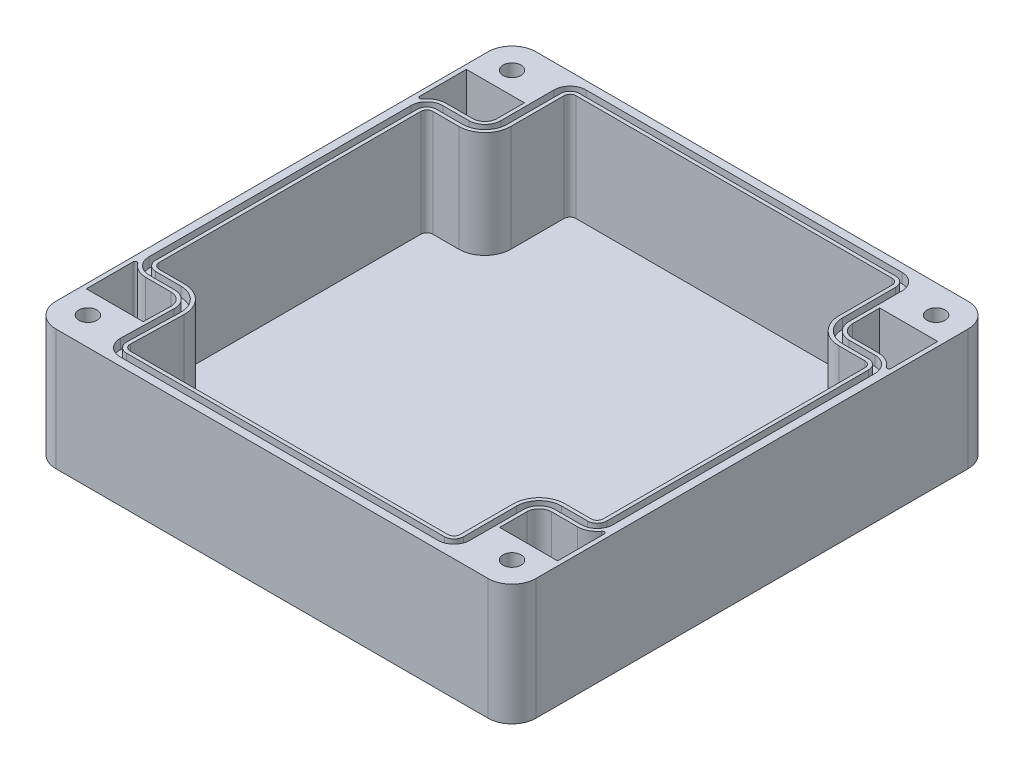
SolidWorks part; units mm, degrees
other "陽光" [suppressed]
material "ABS"
ref_plane "前基準面" through (0, 0, 0) normal (0, 0, 1) x (1, 0, 0)
ref_plane "上基準面" through (0, 0, 0) normal (0, 1, 0) x (1, 0, 0)
ref_plane "右基準面" through (0, 0, 0) normal (1, 0, 0) x (0, 0, -1)
other "ABS"
sketch "草圖1" plane through (0, 0, 0) normal (0, 1, 0) x (1, 0, 0)
  line L1 (6.3409, 120.3409) -> (114.3409, 120.3409)
  line L2 (0.3409, 114.3409) -> (0.3409, 6.3409)
  line L3 (6.3409, 0.3409) -> (114.3409, 0.3409)
  line L4 (120.3409, 114.3409) -> (120.3409, 6.3409)
  circle A0 centre (7.3409, 113.3409) radius 2.25
  circle A2 centre (113.3409, 113.3409) radius 2.25
  circle A5 centre (7.3409, 7.3409) radius 2.25
  circle A7 centre (113.3409, 7.3409) radius 2.25
  arc A8 (114.3409, 120.3409) -> (120.3409, 114.3409) centre (114.3409, 114.3409) cw
  arc A9 (120.3409, 6.3409) -> (114.3409, 0.3409) centre (114.3409, 6.3409) cw
  arc A10 (6.3409, 0.3409) -> (0.3409, 6.3409) centre (6.3409, 6.3409) cw
  arc A11 (0.3409, 114.3409) -> (6.3409, 120.3409) centre (6.3409, 114.3409) cw
  point P37 (120.3409, 120.3409)
  point P42 (0.3409, 0.3409)
  point P45 (0.3409, 120.3409)
  dimension "D3" = 106
  dimension "D4" = 7
  dimension "D7" = 7
  dimension "D13" = 6
  dimension "D6" = 106
  dimension "D2" = 120
  dimension "D8" = 7
  dimension "D10" = 120
  dimension "D12" = 7
extrude "填料-伸長1" add sketch "草圖1" along normal blind 30.25
sketch "草圖2" plane through (0, 30.25, 0) normal (0, 1, 0) x (1, 0, 0)
  line L1 (15.9409, 101.0538) -> (15.9409, 107.8409)
  line L21 (6.3409, 97.9538) -> (12.8409, 97.9538)
  line L23 (6.3281, 22.7581) -> (12.7279, 22.7414)
  line L25 (15.8189, 19.567) -> (15.6575, 12.8409)
  line L29 (0.3409, 114.3409) -> (0.3409, 6.3409) construction
  line L34 (114.3409, 120.3409) -> (6.3409, 120.3409) construction
  line L35 (99.8409, 115.8409) -> (20.8409, 115.8409)
  line L36 (19.3409, 101.0538) -> (19.3409, 114.3409)
  line L37 (6.3409, 94.5538) -> (12.8409, 94.5538)
  line L42 (4.8409, 93.0538) -> (4.8409, 27.6581)
  line L47 (0.3409, 60.3409) -> (120.3409, 60.3409) construction
  line L48 (104.7409, 19.628) -> (104.7409, 12.8409)
  line L49 (120.3409, 6.3409) -> (120.3409, 114.3409) construction
  line L50 (60.3409, 120.3409) -> (60.3409, 0.3409) construction
  line L51 (114.3409, 22.728) -> (107.8409, 22.728)
  line L52 (6.3409, 0.3409) -> (114.3409, 0.3409) construction
  line L60 (114.3409, 97.9538) -> (107.8409, 97.9538)
  line L61 (104.7409, 101.0538) -> (104.7409, 107.8409)
  line L62 (1.4409, 96.1843) -> (1.4409, 107.8409)
  line L63 (1.4409, 107.8409) -> (15.9409, 107.8409)
  line L64 (6.337, 26.1581) -> (12.7368, 26.1414)
  line L65 (1.4409, 24.5276) -> (1.4409, 12.8409)
  line L66 (1.4409, 12.8409) -> (15.6575, 12.8409)
  line L67 (119.2409, 96.1843) -> (119.2409, 107.8409)
  line L68 (119.2409, 107.8409) -> (104.7409, 107.8409)
  line L69 (119.2409, 24.4975) -> (119.2409, 12.8409)
  line L70 (119.2409, 12.8409) -> (104.7409, 12.8409)
  line L71 (19.2179, 19.4855) -> (18.9034, 6.3769)
  line L72 (20.403, 4.8409) -> (99.8409, 4.8409)
  line L73 (101.3409, 19.628) -> (101.3409, 6.3409)
  line L74 (114.3409, 26.128) -> (107.8409, 26.128)
  line L75 (115.8409, 27.628) -> (115.8409, 93.0538)
  line L76 (114.3409, 94.5538) -> (107.8409, 94.5538)
  line L77 (101.3409, 101.0538) -> (101.3409, 114.3409)
  arc A42 (19.3409, 114.3409) -> (20.8409, 115.8409) centre (20.8409, 114.3409) cw
  arc A43 (1.4409, 24.5276) -> (2.3483, 24.8175) centre (1.9409, 24.5276) cw
  arc A44 (12.8409, 94.5538) -> (19.3409, 101.0538) centre (12.8409, 101.0538) ccw
  arc A45 (2.3483, 95.8944) -> (1.4409, 96.1843) centre (1.9409, 96.1843) cw
  arc A51 (12.8409, 97.9538) -> (15.9409, 101.0538) centre (12.8409, 101.0538) ccw
  arc A52 (6.3409, 97.9538) -> (2.3483, 95.8944) centre (6.3409, 93.0538) ccw
  arc A53 (6.3281, 22.7581) -> (2.3483, 24.8175) centre (6.3409, 27.6581) cw
  arc A54 (15.8189, 19.567) -> (12.7279, 22.7414) centre (12.7198, 19.6414) ccw
  arc A57 (104.7409, 19.628) -> (107.8409, 22.728) centre (107.8409, 19.628) cw
  arc A58 (114.3409, 22.728) -> (118.3335, 24.7874) centre (114.3409, 27.628) ccw
  arc A59 (114.3409, 97.9538) -> (118.3335, 95.8944) centre (114.3409, 93.0538) cw
  arc A60 (107.8409, 97.9538) -> (104.7409, 101.0538) centre (107.8409, 101.0538) cw
  arc A62 (6.3409, 94.5538) -> (4.8409, 93.0538) centre (6.3409, 93.0538) ccw
  arc A63 (6.337, 26.1581) -> (4.8409, 27.6581) centre (6.3409, 27.6581) cw
  arc A64 (19.2179, 19.4855) -> (12.7368, 26.1414) centre (12.7198, 19.6414) ccw
  arc A65 (18.9034, 6.3769) -> (20.403, 4.8409) centre (20.403, 6.3409) ccw
  arc A66 (101.3409, 6.3409) -> (99.8409, 4.8409) centre (99.8409, 6.3409) cw
  arc A67 (119.2409, 96.1843) -> (118.3335, 95.8944) centre (118.7409, 96.1843) cw
  arc A68 (101.3409, 19.628) -> (107.8409, 26.128) centre (107.8409, 19.628) cw
  arc A69 (118.3335, 24.7874) -> (119.2409, 24.4975) centre (118.7409, 24.4975) cw
  arc A70 (114.3409, 26.128) -> (115.8409, 27.628) centre (114.3409, 27.628) ccw
  arc A71 (114.3409, 94.5538) -> (115.8409, 93.0538) centre (114.3409, 93.0538) cw
  arc A72 (107.8409, 94.5538) -> (101.3409, 101.0538) centre (107.8409, 101.0538) cw
  arc A73 (101.3409, 114.3409) -> (99.8409, 115.8409) centre (99.8409, 114.3409) ccw
  point P41 (102.8409, 96.0538)
  point P44 (17.8409, 96.0538)
  point P47 (102.8409, 24.628)
  point P50 (17.8409, 24.628)
  point P52 (99.8409, 3.3409)
  point P54 (117.3409, 27.628)
  point P56 (117.3409, 93.0538)
  point P57 (104.8409, 17.8409)
  point P59 (110.2409, 20.8409)
  point P60 (110.2409, 24.0409)
  point P61 (113.4409, 24.0409)
  point P62 (113.4409, 65.9246)
  point P63 (110.2409, 65.9246)
  point P64 (110.2409, 69.1246)
  point P67 (104.8409, 72.1246)
  point P68 (104.8409, 85.2409)
  point P69 (101.6409, 85.2409)
  point P70 (101.6409, 88.4409)
  point P73 (10.8409, 85.2409)
  point P74 (10.8409, 72.8409)
  point P75 (3.3409, 93.0538)
  point P77 (5.4409, 69.8409)
  point P78 (5.4409, 66.6409)
  point P79 (2.2409, 66.6409)
  point P80 (2.2409, 24.0409)
  point P81 (5.4409, 24.0409)
  point P82 (5.4409, 20.8409)
  point P83 (3.3409, 27.6581)
  point P85 (10.5331, 17.8409)
  point P86 (10.5331, 5.4409)
  point P87 (20.403, 3.3409)
  point P88 (99.8409, 119.2409)
  point P89 (20.8409, 119.2409)
  point P91 (104.8409, 5.4409)
  point P92 (15.9409, 114.3409)
  point P98 (1.4409, 93.0538)
  point P105 (15.5044, 6.4585)
  point P107 (20.403, 1.4409)
  point P108 (99.8409, 1.4409)
  point P110 (104.7409, 6.3409)
  point P116 (119.2409, 27.628)
  point P117 (119.2409, 93.0538)
  point P123 (104.7409, 114.3409)
extrude "除料-伸長1" cut sketch "草圖2" against normal blind 26.6
sketch "草圖3" plane through (0, 30.25, 0) normal (0, 1, 0) x (1, 0, 0)
  line L0 (114.3409, 95.4538) -> (107.8409, 95.4538)
  line L1 (116.7409, 27.628) -> (116.7409, 93.0538)
  line L2 (107.8409, 25.228) -> (114.3409, 25.228)
  line L3 (102.2409, 6.3409) -> (102.2409, 19.628)
  line L4 (20.403, 3.9409) -> (99.8409, 3.9409)
  line L5 (18.3182, 19.507) -> (18.0037, 6.3985)
  line L6 (6.3346, 25.2581) -> (12.7345, 25.2414)
  line L7 (3.9409, 93.0538) -> (3.9409, 27.6581)
  line L8 (12.8409, 95.4538) -> (6.3409, 95.4538)
  line L9 (18.4409, 114.3409) -> (18.4409, 101.0538)
  line L10 (99.8409, 116.7409) -> (20.8409, 116.7409)
  line L11 (102.2409, 101.0538) -> (102.2409, 114.3409)
  line L36 (103.8409, 101.0538) -> (103.8409, 114.3409)
  line L37 (99.8409, 118.3409) -> (20.8409, 118.3409)
  line L38 (16.8409, 114.3409) -> (16.8409, 101.0538)
  line L39 (12.8409, 97.0538) -> (6.3409, 97.0538)
  line L40 (2.3409, 93.0538) -> (2.3409, 27.6581)
  line L41 (6.3304, 23.6581) -> (12.7303, 23.6414)
  line L42 (16.7187, 19.5454) -> (16.4041, 6.4369)
  line L43 (20.403, 2.3409) -> (99.8409, 2.3409)
  line L44 (103.8409, 6.3409) -> (103.8409, 19.628)
  line L45 (107.8409, 23.628) -> (114.3409, 23.628)
  line L46 (118.3409, 27.628) -> (118.3409, 93.0538)
  line L47 (114.3409, 97.0538) -> (107.8409, 97.0538)
  arc A0 (102.2409, 101.0538) -> (107.8409, 95.4538) centre (107.8409, 101.0538) ccw
  arc A1 (116.7409, 93.0538) -> (114.3409, 95.4538) centre (114.3409, 93.0538) ccw
  arc A2 (114.3409, 25.228) -> (116.7409, 27.628) centre (114.3409, 27.628) ccw
  arc A3 (107.8409, 25.228) -> (102.2409, 19.628) centre (107.8409, 19.628) ccw
  arc A4 (99.8409, 3.9409) -> (102.2409, 6.3409) centre (99.8409, 6.3409) ccw
  arc A5 (18.0037, 6.3985) -> (20.403, 3.9409) centre (20.403, 6.3409) ccw
  arc A6 (18.3182, 19.507) -> (12.7345, 25.2414) centre (12.7198, 19.6414) ccw
  arc A7 (3.9409, 27.6581) -> (6.3346, 25.2581) centre (6.3409, 27.6581) ccw
  arc A8 (6.3409, 95.4538) -> (3.9409, 93.0538) centre (6.3409, 93.0538) ccw
  arc A9 (12.8409, 95.4538) -> (18.4409, 101.0538) centre (12.8409, 101.0538) ccw
  arc A10 (20.8409, 116.7409) -> (18.4409, 114.3409) centre (20.8409, 114.3409) ccw
  arc A11 (102.2409, 114.3409) -> (99.8409, 116.7409) centre (99.8409, 114.3409) ccw
  arc A36 (103.8409, 101.0538) -> (107.8409, 97.0538) centre (107.8409, 101.0538) ccw
  arc A37 (103.8409, 114.3409) -> (99.8409, 118.3409) centre (99.8409, 114.3409) ccw
  arc A38 (20.8409, 118.3409) -> (16.8409, 114.3409) centre (20.8409, 114.3409) ccw
  arc A39 (12.8409, 97.0538) -> (16.8409, 101.0538) centre (12.8409, 101.0538) ccw
  arc A40 (6.3409, 97.0538) -> (2.3409, 93.0538) centre (6.3409, 93.0538) ccw
  arc A41 (2.3409, 27.6581) -> (6.3304, 23.6581) centre (6.3409, 27.6581) ccw
  arc A42 (16.7187, 19.5454) -> (12.7303, 23.6414) centre (12.7198, 19.6414) ccw
  arc A43 (16.4041, 6.4369) -> (20.403, 2.3409) centre (20.403, 6.3409) ccw
  arc A44 (99.8409, 2.3409) -> (103.8409, 6.3409) centre (99.8409, 6.3409) ccw
  arc A45 (107.8409, 23.628) -> (103.8409, 19.628) centre (107.8409, 19.628) ccw
  arc A46 (114.3409, 23.628) -> (118.3409, 27.628) centre (114.3409, 27.628) ccw
  arc A47 (118.3409, 93.0538) -> (114.3409, 97.0538) centre (114.3409, 93.0538) ccw
  dimension "D1" = 1.6
extrude "除料-伸長2" cut sketch "草圖3" against normal blind 2.5
